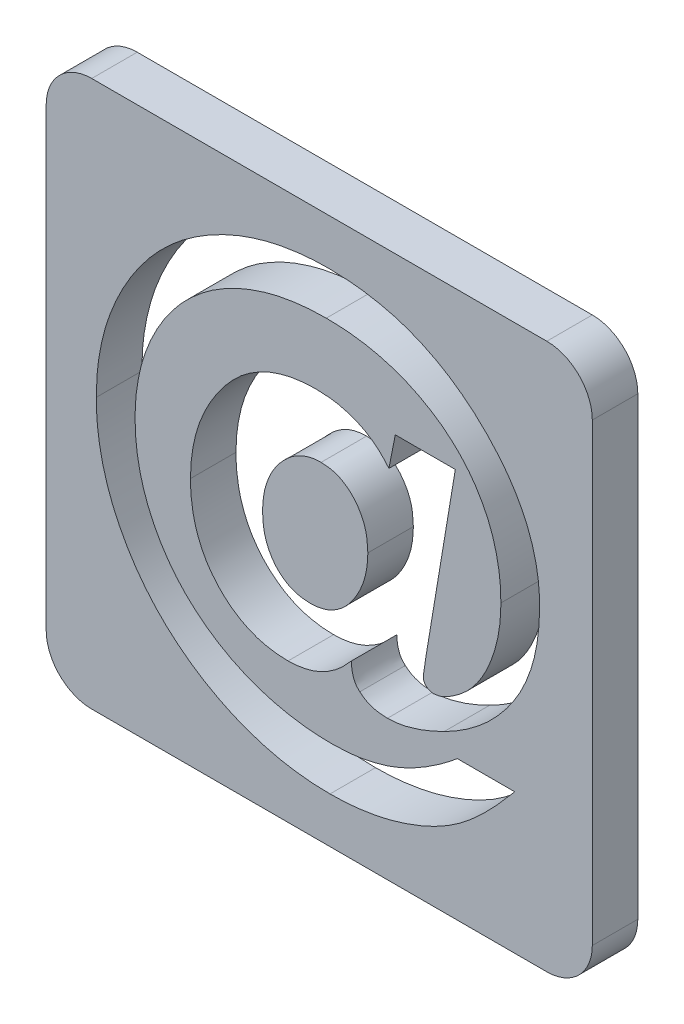
SolidWorks part; units mm, degrees
ref_plane "Front Plane" through (0, 0, 0) normal (0, 0, 1) x (1, 0, 0)
ref_plane "Top Plane" through (0, 0, 0) normal (0, 1, 0) x (1, 0, 0)
ref_plane "Right Plane" through (0, 0, 0) normal (1, 0, 0) x (0, 0, -1)
sketch "Sketch1" plane through (0, 0, 0) normal (0, 0, 1) x (1, 0, 0)
  line L1 (-50, 60) -> (50, 60)
  line L2 (-60, 50) -> (-60, -50)
  line L3 (-50, -60) -> (50, -60)
  line L4 (60, 50) -> (60, -50)
  line L5 (-60, 60) -> (60, -60) construction
  line L6 (-60, -60) -> (60, 60) construction
  arc A0 (-60, -50) -> (-50, -60) centre (-50, -50) ccw
  arc A1 (50, -60) -> (60, -50) centre (50, -50) ccw
  arc A2 (50, 60) -> (60, 50) centre (50, 50) cw
  arc A3 (-50, 60) -> (-60, 50) centre (-50, 50) ccw
  point P0 (0, 0)
  dimension "D3" = 10
  dimension "D1" = 120
  dimension "D2" = 120
extrude "Boss-Extrude1" add sketch "Sketch1" along normal blind 10 contours A3 L2 A0 L3 A1 L4 A2 L1
sketch "Sketch2" plane through (0, 0, 10) normal (0, 0, 1) x (1, 0, 0)
  line L0 (0, 0) -> (0, 40) construction
  line L1 (-50, 50) -> (50, 50) construction
  line L2 (-50, 50) -> (-50, -50) construction
  line L3 (-50, -50) -> (50, -50) construction
  line L4 (50, 50) -> (50, -50) construction
  line L5 (-50, 50) -> (50, -50) construction
  line L6 (-50, -50) -> (50, 50) construction
  line L7 (0, 40) -> (-40, 40) construction
  line L8 (-40, 40) -> (-40, 0) construction
  line L9 (-40, 0) -> (0, 0) construction
  line L11 (0, 20) -> (-20, 20) construction
  line L12 (-20, 40) -> (-20, 20) construction
  circle A0 centre (0, 40) radius 4 construction
  circle A1 centre (0, 20) radius 4 construction
  circle A2 centre (0, 0) radius 4 construction
  circle A3 centre (-20, 20) radius 4 construction
  circle A4 centre (-20, 40) radius 4 construction
  circle A5 centre (-40, 40) radius 4 construction
  circle A6 centre (0, 0) radius 4 construction
  circle A7 centre (20, 0) radius 4 construction
  circle A8 centre (40, 0) radius 4 construction
  circle A9 centre (40, 20) radius 4 construction
  circle A10 centre (40, 40) radius 4 construction
  circle A11 centre (20, 20) radius 4 construction
  circle A12 centre (0, 0) radius 4 construction
  circle A13 centre (0, -20) radius 4 construction
  circle A14 centre (0, -40) radius 4 construction
  circle A15 centre (20, -40) radius 4 construction
  circle A16 centre (40, -40) radius 4 construction
  circle A17 centre (20, -20) radius 4 construction
  circle A18 centre (0, 0) radius 4 construction
  circle A19 centre (-20, 0) radius 4 construction
  circle A20 centre (-40, 0) radius 4 construction
  circle A21 centre (-40, -20) radius 4 construction
  circle A22 centre (-40, -40) radius 4 construction
  circle A23 centre (-20, -20) radius 4 construction
  text T0 "@" font "Century Gothic" height 95
  point P0 (0, 0)
  point P55 (0, 0)
  dimension "D4" = 8
  dimension "D1" = 100
  dimension "D2" = 100
  dimension "D3" = 40
  dimension "D5" = 4
extrude "Cut-Extrude10" cut sketch "Sketch2" against normal blind 10
